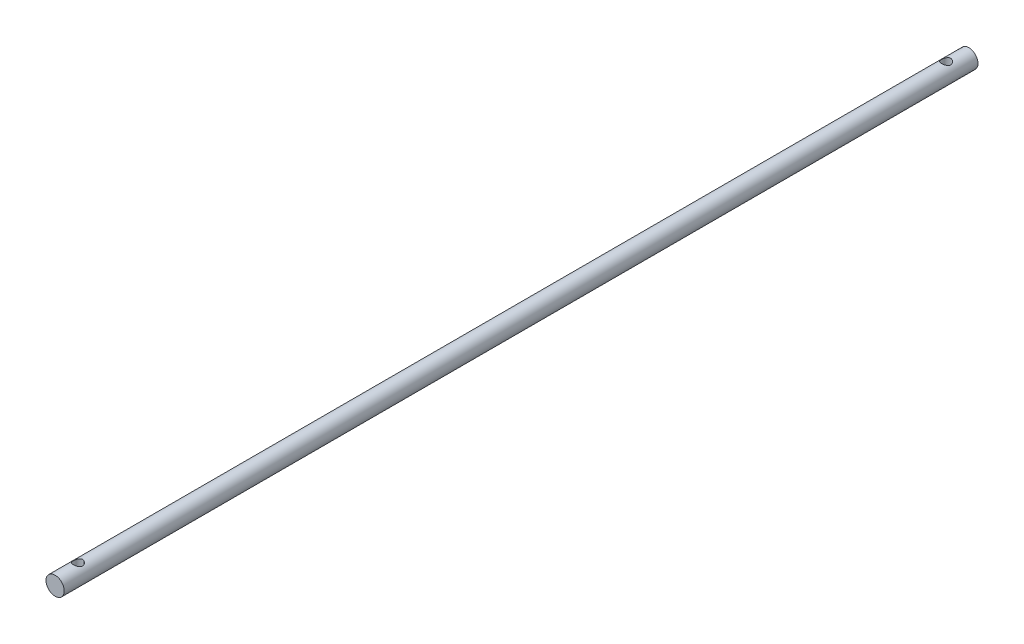
SolidWorks part; units mm, degrees
material "Plain Carbon Steel"
ref_plane "Front Plane" through (0, 0, 0) normal (0, 0, 1) x (1, 0, 0)
ref_plane "Top Plane" through (0, 0, 0) normal (0, 1, 0) x (1, 0, 0)
ref_plane "Right Plane" through (0, 0, 0) normal (1, 0, 0) x (0, 0, -1)
sketch "Sketch1" plane through (0, 0, 0) normal (0, 0, 1) x (1, 0, 0)
  circle A0 centre (0, 0) radius 4
extrude "Extrude1" add sketch "Sketch1" along normal blind 400
hole_wizard "Ø4.0 (4) Diameter Hole1" positions "Sketch4" profile "Sketch3" hole size "Ø4.0" standard "Ansi Metric"
sketch "Sketch4" plane through (0, 0, 0) normal (0, 1, 0) x (1, 0, 0)
  line L0 (4, 0) -> (-4, 0) construction
  line L1 (-4, -400) -> (4, -400) construction
  point P1 (0, -10)
  point P3 (0, -390)
  dimension "D1" = 10
  dimension "D2" = 10
sketch "Sketch3" plane through (0, 0, 10) normal (1, 0, 0) x (0, 0, -1)
  line L0 (0, 0) -> (0, 4)
  line L1 (0, 4) -> (2, 4)
  line L2 (2, 4) -> (2, 0)
  line L5 (2, 0) -> (0, 0)
  line L11 (0, -6.35) -> (0, 107.95) construction
  dimension "Thru Hole Dia." = 4
  dimension "Thru Hole Depth" = 4
